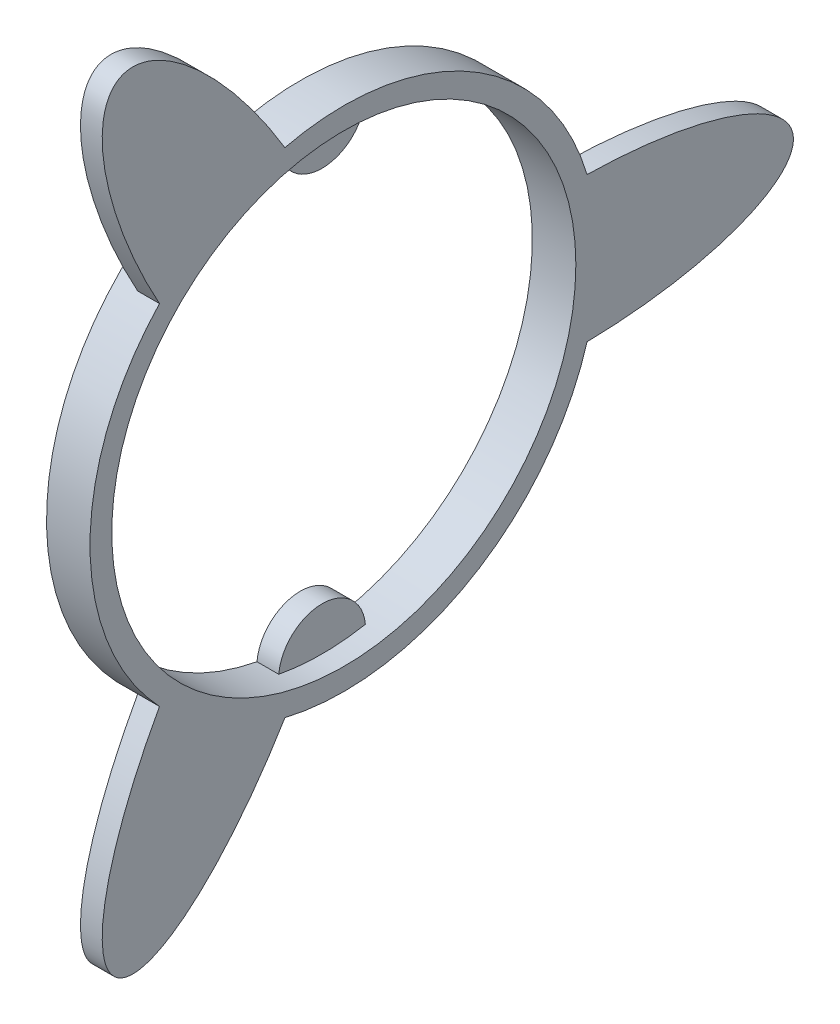
SolidWorks part; units mm, degrees
ref_plane "Front Plane" through (0, 0, 0) normal (0, 0, 1) x (1, 0, 0)
ref_plane "Top Plane" through (0, 0, 0) normal (0, 1, 0) x (1, 0, 0)
ref_plane "Right Plane" through (0, 0, 0) normal (1, 0, 0) x (0, 0, -1)
sketch "Sketch1" plane through (0, 0, 0) normal (1, 0, 0) x (0, 0, -1)
  circle A0 centre (0, 0) radius 17.5
  circle A1 centre (0, 0) radius 16
extrude "Boss-Extrude1" add sketch "Sketch1" along normal blind 3
sketch "Sketch2" plane through (3, 0, 0) normal (1, 0, 0) x (0, 0, -1)
  line L0 (0, 0) -> (-8, 13.8564)
  line L5 (0, 0) -> (16, 0)
  line L6 (0, 0) -> (-8, -13.8564)
  line L7 (55, 0) -> (-55, 0) construction
  ellipse E0 centre (-8, -13.8564) end of major axis (-15.5, -26.8468) minor radius 5
  ellipse E1 centre (-8, 13.8564) end of major axis (-0.5, 0.866) minor radius 5
  ellipse E2 centre (16, 0) end of major axis (1, 0) minor radius 5
  circle M11 centre (0, 0) radius 17.5
extrude "Boss-Extrude2" add sketch "Sketch2" against normal blind 1.5 contours E1 M11 | E2 M11 | E0 M11
sketch "Sketch3" plane through (0, 0, 0) normal (-1, 0, 0) x (0, 0, 1)
  line L0 (55, 0) -> (-55, 0) construction
  line L1 (3, -16) -> (-3, -16)
  line L2 (3, 16) -> (-3, 16)
  arc A2 (3, -16) -> (-3, -16) centre (0, -16) ccw
  arc A3 (3, 16) -> (-3, 16) centre (0, 16) cw
extrude "Boss-Extrude3" add sketch "Sketch3" against normal blind 1.5
